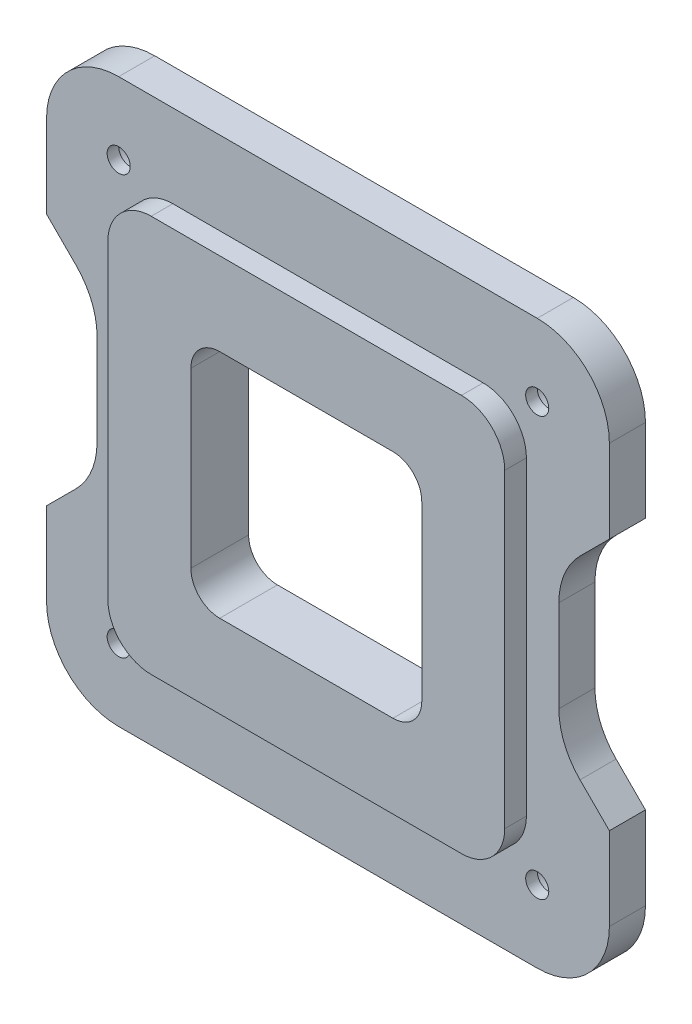
SolidWorks part; units mm, degrees
ref_plane "Front Plane" through (0, 0, 0) normal (0, 0, 1) x (1, 0, 0)
ref_plane "Top Plane" through (0, 0, 0) normal (0, 1, 0) x (1, 0, 0)
ref_plane "Right Plane" through (0, 0, 0) normal (1, 0, 0) x (0, 0, -1)
sketch "Sketch1" plane through (0, 0, 0) normal (0, 0, 1) x (1, 0, 0)
  line L0 (0, -39) -> (0, 39) construction
  line L1 (-29, 39) -> (29, 39)
  line L2 (-39, 29) -> (-39, 17.5)
  line L3 (-29, -39) -> (29, -39)
  line L4 (39, 29) -> (39, 17.5)
  line L5 (-29, -29) -> (-29, 29) construction
  line L6 (-29, 29) -> (29, 29) construction
  line L7 (-39, -17.5) -> (-34.9289, -13.4289)
  line L8 (-32, -6.3579) -> (-32, 6.3579)
  line L9 (0, 21.2748) -> (0, 0) construction
  line L10 (-87.7649, 0) -> (-84.8849, 0) construction
  line L11 (-39, 17.5) -> (-34.9289, 13.4289)
  line L12 (-39, -17.5) -> (-39, -29)
  line L13 (-39, 0) -> (-39, -17.5) construction
  line L14 (-39, 17.5) -> (-39, 0) construction
  line L15 (39, 17.5) -> (34.9289, 13.4289)
  line L16 (32, -6.3579) -> (32, 6.3579)
  line L17 (39, -17.5) -> (34.9289, -13.4289)
  line L18 (39, -17.5) -> (39, -29)
  line L19 (39, 0) -> (39, -17.5) construction
  line L20 (39, 17.5) -> (39, 0) construction
  arc A0 (-39, -29) -> (-29, -39) centre (-29, -29) ccw
  arc A1 (29, -39) -> (39, -29) centre (29, -29) ccw
  arc A2 (39, 29) -> (29, 39) centre (29, 29) ccw
  arc A3 (-29, 39) -> (-39, 29) centre (-29, 29) ccw
  circle A4 centre (-29, 29) radius 2.75 construction
  circle A5 centre (29, 29) radius 2.75 construction
  circle A6 centre (29, -29) radius 2.75 construction
  circle A7 centre (-29, -29) radius 2.75 construction
  arc A8 (34.9289, 13.4289) -> (32, 6.3579) centre (42, 6.3579) ccw
  arc A9 (32, -6.3579) -> (34.9289, -13.4289) centre (42, -6.3579) ccw
  arc A10 (-34.9289, 13.4289) -> (-32, 6.3579) centre (-42, 6.3579) cw
  arc A11 (-32, -6.3579) -> (-34.9289, -13.4289) centre (-42, -6.3579) cw
  point P32 (-32, 0)
  point P41 (32, 10.5)
  point P44 (32, -10.5)
  point P47 (-32, 10.5)
  point P50 (-32, -10.5)
  dimension "D1" = 10
  dimension "D2" = 5.5
  dimension "D7" = 10
  dimension "D3" = 58
  dimension "D4" = 135
  dimension "D5" = 32
  dimension "D6" = 35
extrude "Boss-Extrude1" add sketch "Sketch1" along normal blind 5
sketch "Sketch2" plane through (0, 0, 5) normal (0, 0, -1) x (-1, 0, 0)
  line L0 (0, 27.5) -> (0, -27.5) construction
  line L1 (-21.5, 27.5) -> (21.5, 27.5)
  line L2 (-27.5, 21.5) -> (-27.5, -21.5)
  line L3 (-21.5, -27.5) -> (21.5, -27.5)
  line L4 (27.5, 21.5) -> (27.5, -21.5)
  arc A0 (27.5, 21.5) -> (21.5, 27.5) centre (21.5, 21.5) ccw
  arc A1 (27.5, -21.5) -> (21.5, -27.5) centre (21.5, -21.5) cw
  arc A2 (-27.5, -21.5) -> (-21.5, -27.5) centre (-21.5, -21.5) ccw
  arc A3 (-27.5, 21.5) -> (-21.5, 27.5) centre (-21.5, 21.5) cw
  dimension "D1" = 6
  dimension "D2" = 55
extrude "Boss-Extrude2" add sketch "Sketch2" against normal blind 3
sketch "Sketch3" plane through (0, 0, 0) normal (0, 0, -1) x (-1, 0, 0)
  line L1 (-12, -16) -> (12, -16)
  line L2 (-16, -12) -> (-16, 12)
  line L3 (-12, 16) -> (12, 16)
  line L4 (16, -12) -> (16, 12)
  circle A0 centre (0, 0) radius 16 construction
  arc A1 (-16, -12) -> (-12, -16) centre (-12, -12) ccw
  arc A2 (12, -16) -> (16, -12) centre (12, -12) ccw
  arc A3 (16, 12) -> (12, 16) centre (12, 12) ccw
  arc A4 (-12, 16) -> (-16, 12) centre (-12, 12) ccw
  dimension "D1" = 32
  dimension "D2" = 4
extrude "Cut-Extrude1" cut sketch "Sketch3" against normal through all both and the other way through all
sketch "Sketch4" plane through (0, 0, 0) normal (0, 0, -1) x (-1, 0, 0)
  point P0 (-29, -29)
  point P3 (29, -29)
  point P6 (29, 29)
  point P9 (-29, 29)
hole_wizard "Tap Drill for M4 Tap1" positions "Sketch4" profile "Sketch5" hole size "M4" standard "DIN"
sketch "Sketch5" plane through (29, -29, 0) normal (1, 0, 0) x (0, 1, 0)
  line L0 (0, 0) -> (0, 10.9914)
  line L1 (0, 10.9914) -> (1.65, 10)
  line L2 (1.65, 10) -> (1.65, 0)
  line L5 (1.65, 0) -> (0, 0)
  line L10 (0, 10.9914) -> (-1.65, 10) construction
  line L11 (0, -6.35) -> (0, 107.95) construction
  dimension "Hole Dia." = 3.3
  dimension "Hole Depth" = 10
  dimension "Drill Angle" = 118
sketch "Sketch6" plane through (0, 0, 0) normal (0, 0, -1) x (-1, 0, 0)
  point P0 (29, -29)
  point P3 (29, 29)
  point P6 (-29, 29)
  point P9 (-29, -29)
hole_wizard "CBORE for M3 Hex Socket Head Cap Screw1" positions "Sketch6" profile "Sketch7" counterbore size "M3" standard "DIN" end condition through all
sketch "Sketch7" plane through (-29, -29, 0) normal (1, 0, 0) x (0, 1, 0)
  line L0 (0, 0) -> (0, 8)
  line L1 (0, 8) -> (1.6, 8)
  line L3 (1.6, 8) -> (1.6, 3.4)
  line L4 (1.6, 3.4) -> (3.25, 3.4)
  line L5 (3.25, 3.4) -> (3.25, 0)
  line L7 (3.25, 0) -> (0, 0)
  line L11 (0, -6.35) -> (0, 107.95) construction
  dimension "Thru Hole Dia." = 3.2
  dimension "Thru Hole Depth" = 8
  dimension "C'Bore Dia." = 6.5
  dimension "C'Bore Depth" = 3.4
